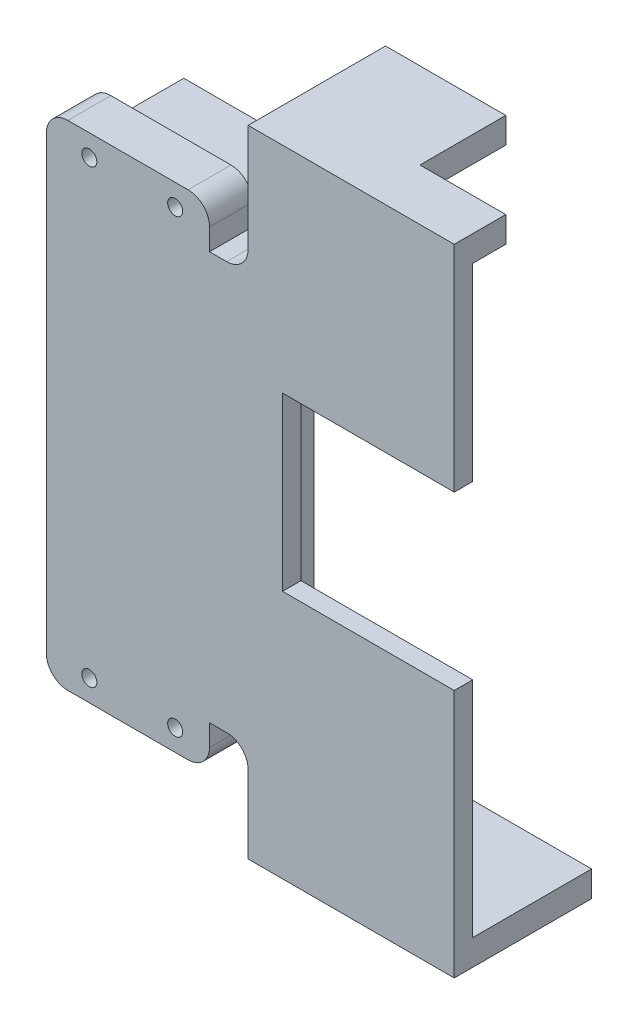
SolidWorks part; units mm, degrees
material "ABS"
ref_plane "前视基准面" through (0, 0, 0) normal (0, 0, 1) x (1, 0, 0)
ref_plane "上视基准面" through (0, 0, 0) normal (0, 1, 0) x (1, 0, 0)
ref_plane "右视基准面" through (0, 0, 0) normal (1, 0, 0) x (0, 0, -1)
sketch "草图1" plane through (0, 0, 0) normal (0, 1, 0) x (1, 0, 0)
  line L1 (-65, -32) -> (65, -32)
  line L2 (-65, -32) -> (-65, 32)
  line L3 (-65, 32) -> (65, 32)
  line L4 (65, -32) -> (65, 32)
  line L5 (-65, -32) -> (65, 32) construction
  line L6 (-65, 32) -> (65, -32) construction
  point P0 (0, 0)
  dimension "D1" = 64
  dimension "D2" = 130
extrude "凸台-拉伸1" add sketch "草图1" along normal blind 125
sketch "草图2" plane through (65, 0, 0) normal (1, 0, 0) x (0, 0, -1)
  line L0 (0, 0) -> (0, 39.3127) construction
  line L1 (-27.7, 5) -> (27.7, 5)
  line L2 (-27.7, 5) -> (-27.7, 119)
  line L3 (-27.7, 119) -> (27.7, 119)
  line L4 (27.7, 5) -> (27.7, 119)
  line L5 (-32, 0) -> (32, 0) construction
  dimension "D1" = 55.4
  dimension "D2" = 114
  dimension "D3" = 5
extrude "切除-拉伸1" cut sketch "草图2" against normal blind 47
sketch "草图3" plane through (18, 0, 0) normal (1, 0, 0) x (0, 0, -1)
  line L0 (-27.7, 5) -> (27.7, 5) construction
  line L1 (-22.7, 91) -> (22.7, 91)
  line L2 (-22.7, 91) -> (-22.7, 5)
  line L3 (-22.7, 5) -> (22.7, 5)
  line L4 (22.7, 91) -> (22.7, 5)
  line L5 (0, 0) -> (0, 26.028) construction
  line L6 (27.7, 119) -> (-27.7, 119) construction
  dimension "D1" = 28
  dimension "D2" = 45.4
extrude "切除-拉伸2" cut sketch "草图3" against normal blind 78
sketch "草图4" plane through (65, 0, 0) normal (1, 0, 0) x (0, 0, -1)
  line L0 (-32, 0) -> (32, 0) construction
  line L1 (14.5499, 75) -> (38.5888, 75)
  line L2 (14.5499, 75) -> (14.5499, 35)
  line L3 (14.5499, 35) -> (38.5888, 35)
  line L4 (38.5888, 75) -> (38.5888, 35)
  dimension "D1" = 35
  dimension "D2" = 40
extrude "切除-拉伸3" cut sketch "草图4" against normal blind 40
sketch "草图5" plane through (65, 0, 0) normal (1, 0, 0) x (0, 0, -1)
  line L0 (32, 125) -> (32, 75) construction
  line L1 (27.7, 75) -> (32, 75)
  line L2 (27.7, 75) -> (27.7, 100)
  line L3 (27.7, 100) -> (32, 100)
  line L4 (32, 75) -> (32, 100)
  line L5 (27.7, 75) -> (27.7, 119) construction
  line L6 (-32, 125) -> (32, 125) construction
  point P7 (0, 0)
  point P8 (27.7, 75)
  dimension "D1" = 25
  dimension "D2" = 25
extrude "切除-拉伸4" cut sketch "草图5" against normal blind 25 contours L2 L1 L4 L3
sketch "草图6" plane through (0, 125, 0) normal (0, 1, 0) x (1, 0, 0)
  line L0 (0, 0) -> (40.4194, 0) construction
  line L1 (50, 20) -> (40, 20)
  line L2 (50, 20) -> (50, -20)
  line L3 (50, -20) -> (40, -20)
  line L4 (40, 20) -> (40, -20)
  line L5 (65, -32) -> (65, 32) construction
  dimension "D1" = 40
  dimension "D2" = 10
  dimension "D3" = 15
extrude "切除-拉伸5" cut sketch "草图6" against normal blind 35
sketch "草图9" plane through (0, 0, 32) normal (0, 0, 1) x (1, 0, 0)
  line L0 (-65, 125) -> (65, 125) construction
  line L1 (60, 125) -> (65, 125)
  line L2 (60, 125) -> (60, 0)
  line L3 (60, 0) -> (65, 0)
  line L4 (65, 125) -> (65, 0)
  dimension "D1" = 5
extrude "切除-拉伸8" cut sketch "草图9" against normal through all
sketch "草图10" plane through (0, 0, -32) normal (0, 0, -1) x (-1, 0, 0)
  line L0 (-60, 0) -> (65, 0) construction
  line L1 (5, -17.5) -> (25, -17.5)
  line L2 (5, -17.5) -> (5, 132.5)
  line L3 (5, 132.5) -> (25, 132.5)
  line L4 (25, -17.5) -> (25, 132.5)
  line L5 (5, -17.5) -> (25, 132.5) construction
  line L6 (5, 132.5) -> (25, -17.5) construction
  line L7 (65, 125) -> (65, 0) construction
  point P0 (15, 57.5)
  dimension "D1" = 20
  dimension "D2" = 150
  dimension "D3" = 57.5
  dimension "D4" = 40
extrude "凸台-拉伸2" add sketch "草图10" against normal blind 5
sketch "草图11" plane through (0, 0, -27) normal (0, 0, 1) x (1, 0, 0)
  line L0 (60, 62.5) -> (6.0472, 62.5) construction
  line L1 (60, 125) -> (60, 0) construction
  line L2 (-65, 0) -> (60, 0) construction
  line L3 (-5, 0) -> (-5, -17.5) construction
  circle A0 centre (-15, -12) radius 2.5
  circle A1 centre (-15, 137) radius 2.5
  dimension "D1" = 5
  dimension "D2" = 12
  dimension "D3" = 10
extrude "切除-拉伸9" cut sketch "草图11" against normal through all
fillet "圆角1" radius 3 10 edges at (-15, 0, -27) (-15, 125, -27) (-25, 125, -29.5) (-25, 132.5, -29.5) (-5, 125, -29.5) (-5, 132.5, -29.5) (-25, -17.5, -29.5) (-25, 0, -29.5) (-5, 0, -29.5) (-5, -17.5, -29.5)
sketch "草图12" plane through (0, 0, 32) normal (0, 0, 1) x (1, 0, 0)
  line L1 (-65, 125) -> (-33, 125)
  line L2 (-65, 125) -> (-65, 95)
  line L3 (-65, 95) -> (-33, 95)
  line L4 (-33, 125) -> (-33, 95)
  dimension "D1" = 30
  dimension "D2" = 32
extrude "切除-拉伸10" cut sketch "草图12" against normal through all
sketch "草图13" plane through (0, 125, 0) normal (0, 1, 0) x (1, 0, 0)
  line L1 (-33, -32) -> (12, -32)
  line L2 (-33, -32) -> (-33, 18)
  line L3 (-33, 18) -> (12, 18)
  line L4 (12, -32) -> (12, 18)
  dimension "D1" = 50
  dimension "D2" = 45
extrude "切除-拉伸11" cut sketch "草图13" against normal blind 30
fillet "圆角5" radius 5 2 edges at (-33, 110, -18) (12, 110, -18)
sketch "草图14" plane through (-65, 0, 0) normal (-1, 0, 0) x (0, 0, 1)
  line L0 (-27, -17.5) -> (-32, -17.5) construction
  line L1 (-32, 132.5) -> (0, 132.5)
  line L2 (-32, 132.5) -> (-32, -17.5)
  line L3 (-32, -17.5) -> (0, -17.5)
  line L4 (0, 132.5) -> (0, -17.5)
  dimension "D1" = 32
extrude "切除-拉伸12" cut sketch "草图14" against normal through all
sketch "草图16" plane through (60, 0, 0) normal (1, 0, 0) x (0, 0, -1)
  line L1 (-36.5063, 75) -> (-21.6072, 75)
  line L2 (-36.5063, 75) -> (-36.5063, 35)
  line L3 (-36.5063, 35) -> (-21.6072, 35)
  line L4 (-21.6072, 75) -> (-21.6072, 35)
  line L5 (0, 0) -> (-32, 0) construction
  dimension "D1" = 40
  dimension "D2" = 35
extrude "切除-拉伸14" cut sketch "草图16" against normal blind 40
sketch "草图17" plane through (0, 0, 22.7) normal (0, 0, -1) x (-1, 0, 0)
  line L0 (-12, 95) -> (65, 95) construction
  line L1 (35, 95) -> (65, 95)
  line L2 (35, 95) -> (35, 0)
  line L3 (35, 0) -> (65, 0)
  line L4 (65, 95) -> (65, 0)
  line L5 (65, 0) -> (65, 95) construction
  dimension "D1" = 30
extrude "切除-拉伸15" cut sketch "草图17" against normal through all both and the other way through all
sketch "草图18" plane through (40, 0, 0) normal (1, 0, 0) x (0, 0, -1)
  line L4 (-20, 119) -> (0, 119)
  line L5 (0, 119) -> (0, 125)
  line L6 (0, 125) -> (-20, 125)
  line L7 (-20, 125) -> (-20, 119)
  line L8 (-20, 119) -> (0, 119)
  line L9 (0, 119) -> (0, 125)
  line L10 (0, 125) -> (-20, 125)
  line L11 (-20, 125) -> (-20, 119)
  dimension "D1" = 0
extrude "切除-拉伸16" cut sketch "草图18" along normal through all
sketch "草图20" plane through (0, 0, 32) normal (0, 0, 1) x (1, 0, 0)
  line L5 (-35, 95) -> (12, 95) construction
  line L6 (-35, 0) -> (12, 0)
  line L7 (-35, 0) -> (-35, -10)
  line L8 (-35, -10) -> (12, -10)
  line L9 (12, 0) -> (12, -10)
  line L10 (-35, 95) -> (-35, 105)
  line L11 (-35, 105) -> (12, 105)
  line L12 (12, 95) -> (12, 105)
  line L16 (-35, 95) -> (12, 95)
  dimension "D1" = 10
  dimension "D2" = 47
extrude "凸台-拉伸3" add sketch "草图20" against normal blind 10
sketch "草图21" plane through (0, 0, 22) normal (0, 0, -1) x (-1, 0, 0)
  line L0 (-60, 0) -> (35, 0) construction
  line L2 (35, 47.5) -> (-35.0257, 47.5) construction
  line L3 (35, 5) -> (35, 91) construction
  line L4 (-12, 105) -> (35, 105) construction
  line L6 (35, 0) -> (35, -10) construction
  circle A2 centre (25, -5) radius 1.75
  circle A3 centre (5, -5) radius 1.75
  circle A6 centre (5, 100) radius 1.75
  circle A7 centre (25, 100) radius 1.75
  dimension "D2" = 20
  dimension "D3" = 3.5
  dimension "D4" = 10
  dimension "D1" = 5
  dimension "D5" = 5
extrude "切除-拉伸17" cut sketch "草图21" against normal through all
sketch "草图23" plane through (0, 5, 0) normal (0, 1, 0) x (1, 0, 0)
  line L0 (60, 0) -> (-35, 0) construction
  line L1 (60, -27.7) -> (18, -27.7)
  line L2 (60, -27.7) -> (60, 0)
  line L3 (60, 0) -> (18, 0)
  line L4 (18, -27.7) -> (18, 0)
  line L5 (18, -27.7) -> (18, -22.7) construction
extrude "切除-拉伸19" cut sketch "草图23" against normal through all
sketch "草图24" plane through (0, 0, 0) normal (0, 0, -1) x (-1, 0, 0)
  line L0 (-18, 0) -> (-18, -17)
  line L1 (-18, -17) -> (-60, -17)
  line L2 (-60, -17) -> (-60, -23)
  line L3 (-60, -23) -> (-12, -23)
  line L4 (-12, -23) -> (-12, 0)
  line L5 (-18, 0) -> (-12, 0)
  line L6 (-60, 35) -> (-60, 0) construction
  dimension "D1" = 6
  dimension "D2" = 17
extrude "凸台-拉伸4" add sketch "草图24" against normal up to surface (27.7 mm away) up to face at (39.5, 57.25, 27.7)
sketch "草图25" plane through (0, 0, 32) normal (0, 0, 1) x (1, 0, 0)
  line L0 (60, -23) -> (12, -23) construction
  line L1 (12, 0) -> (60, 0)
  line L2 (12, 0) -> (12, -23)
  line L3 (12, -23) -> (60, -23)
  line L4 (60, 0) -> (60, -23)
  line L5 (60, 35) -> (60, 0) construction
extrude "凸台-拉伸5" add sketch "草图25" against normal up to surface (4.3 mm away) up to face at (27.4286, -12.8571, 27.7)
fillet "圆角6" radius 5 4 edges at (12, 105, 27) (-35, 105, 27) (-35, -10, 27) (12, -10, 27)
fillet "圆角8" radius 5 1 edges at (12, 95, 11)
sketch "草图30" plane through (0, 0, 22) normal (0, 0, -1) x (-1, 0, 0)
  line L0 (-7, 105) -> (-3, 105)
  line L1 (-3, 105) -> (-3, 95)
  line L2 (-3, 95) -> (-7, 95)
  line L3 (-7, -10) -> (-3, -10)
  line L4 (-12, 110) -> (-12, 100)
  line L5 (-7, 95) -> (35, 95)
  line L6 (35, 95) -> (35, 100)
  line L7 (30, 105) -> (-7, 105)
  line L8 (-12, 110) -> (-12, 100)
  line L9 (-7, 95) -> (35, 95) construction
  line L10 (35, 95) -> (35, 100) construction
  line L11 (30, 105) -> (-7, 105) construction
  line L12 (-7, -10) -> (30, -10)
  line L13 (35, -5) -> (35, 0)
  line L14 (35, 0) -> (-12, 0)
  line L15 (-12, 0) -> (-12, -15)
  line L16 (-7, -10) -> (30, -10) construction
  line L17 (35, -5) -> (35, 0) construction
  line L18 (35, 0) -> (-12, 0) construction
  line L19 (-12, 0) -> (-12, -15)
  line L20 (-3, -10) -> (-3, 0)
  line L21 (-3, 0) -> (-12, 0)
  arc A2 (30, -10) -> (35, -5) centre (30, -5) ccw
  arc A3 (-12, 100) -> (-7, 95) centre (-7, 100) ccw
  arc A4 (35, 100) -> (30, 105) centre (30, 100) ccw
  arc A5 (-12, 110) -> (-7, 105) centre (-7, 110) ccw
  arc A6 (-12, 100) -> (-7, 95) centre (-7, 100) ccw
  arc A7 (35, 100) -> (30, 105) centre (30, 100) ccw construction
  arc A8 (-12, 110) -> (-7, 105) centre (-7, 110) ccw
  arc A9 (-7, -10) -> (-12, -15) centre (-7, -15) ccw
  arc A10 (30, -10) -> (35, -5) centre (30, -5) ccw construction
  arc A11 (-7, -10) -> (-12, -15) centre (-7, -15) ccw
  dimension "D3" = 4
  dimension "D4" = 4
  dimension "D1" = 0
  dimension "D2" = 0
extrude "切除-拉伸23" cut sketch "草图30" against normal blind 10
sketch "草图31" plane through (12, 0, 0) normal (-1, 0, 0) x (0, 0, 1)
  circle A0 centre (23.7, 113.3) radius 1.55 construction
  circle A1 centre (23.7, -12.3) radius 1.55 construction
  circle A2 centre (23.7, 113.3) radius 1.55
  circle A3 centre (23.7, -12.3) radius 1.55
extrude "切除-拉伸24" cut sketch "草图31" against normal through all
fillet "圆角9" radius 5 1 edges at (12, 0, 16)
fillet "圆角10" radius 5 1 edges at (3, -10, 27)
fillet "圆角11" radius 5 1 edges at (3, 105, 27)
